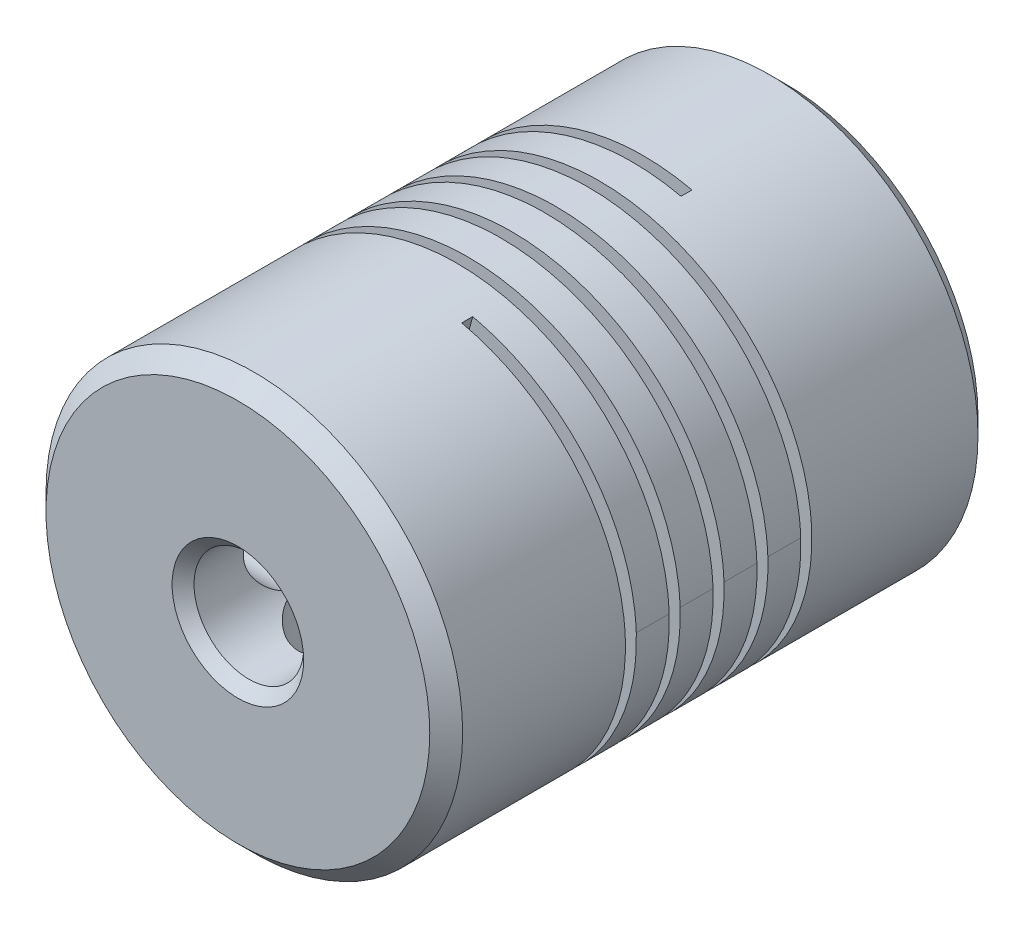
SolidWorks part; units mm, degrees
material "7075-T6 (SN)"
ref_plane "Спереди" through (0, 0, 0) normal (0, 0, 1) x (1, 0, 0)
ref_plane "Сверху" through (0, 0, 0) normal (0, 1, 0) x (1, 0, 0)
ref_plane "Справа" through (0, 0, 0) normal (1, 0, 0) x (0, 0, -1)
sketch "Эскиз1" plane through (0, 0, 0) normal (0, 0, 1) x (1, 0, 0)
  circle A0 centre (0, 0) radius 9.5
  dimension "D1" = 19
extrude "Body" add sketch "Эскиз1" along normal blind 25
sketch "Эскиз2" plane through (0, 0, 25) normal (0, 0, 1) x (1, 0, 0)
  circle A0 centre (0, 0) radius 2.5
  dimension "D1" = 5
extrude "RodHole" cut sketch "Эскиз2" against normal blind 42
chamfer "OuterChamfer" distance 0.75 angle 45 2 edges at (9.5, 0, 25) (9.5, 0, 0)
chamfer "InnerChamfer" distance 0.5 angle 45 2 edges at (2.5, 0, 25) (2.5, 0, 0)
sketch "Эскиз3" plane through (0, 0, 0) normal (1, 0, 0) x (0, 0, -1)
  circle A0 centre (-4.5, 0) radius 1.75
  circle A1 centre (-20.5, 0) radius 1.75
  dimension "D1" = 3.5
  dimension "D2" = 3.5
  dimension "D3" = 4.5
  dimension "D4" = 20.5
extrude "SetScrewHoles1" cut sketch "Эскиз3" against normal blind 12
cosmetic thread "Условное изображение резьбы1" parameters "D2"=4
cosmetic thread "Условное изображение резьбы2" parameters "D2"=4
sketch "Эскиз4" plane through (0, 0, 0) normal (0, 1, 0) x (1, 0, 0)
  circle A0 centre (0, -4.5) radius 1.75
  circle A1 centre (0, -20.5) radius 1.75
  dimension "D1" = 3.5
  dimension "D2" = 3.5
  dimension "D3" = 4.5
  dimension "D4" = 20.5
extrude "SetScrewHoles2" cut sketch "Эскиз4" against normal blind 12
cosmetic thread "Условное изображение резьбы3" parameters "D2"=4
cosmetic thread "Условное изображение резьбы4" parameters "D2"=4
ref_plane "ReferencePlane1" through (0, 0, 17) normal (0, 0, 1) x (1, 0, 0)
sketch "Эскиз6" plane through (0, 0, 17) normal (0, 0, 1) x (1, 0, 0)
  circle A0 centre (0, 0) radius 9.5
curve "SlotTrajectory" pitch 2 height 10 turns 5
ref_plane "ReferencePlane2" through (0, 0, 0) normal (0.9659, -0.2588, 0) x (0, 0, -1)
sketch "Эскиз7" plane through (0, 0, 0) normal (0.9659, -0.2588, 0) x (0, 0, -1)
  line L0 (-0.75, 9.5) -> (-24.25, 9.5) construction
  line L1 (-6.75, 10.0798) -> (-7.25, 10.0798)
  line L2 (-6.75, 10.0798) -> (-6.75, 1.4319)
  line L3 (-6.75, 1.4319) -> (-7.25, 1.4319)
  line L4 (-7.25, 10.0798) -> (-7.25, 1.4319)
  spline S0 degree 3 poles (-17, 9.5) (-16.9586, 9.5) (-16.8749, 9.0054) (-16.75, 6.8924) (-16.625, 3.7301) (-16.5, 0) (-16.375, -3.7301) (-16.25, -6.8924) (-16.125, -9.0054) (-16, -9.7473) (-15.875, -9.0054) (-15.75, -6.8924) (-15.625, -3.7301) (-15.5, 0) (-15.375, 3.7301) (-15.25, 6.8924) (-15.125, 9.0054) (-15, 9.7473) (-14.875, 9.0054) (-14.75, 6.8924) (-14.625, 3.7301) (-14.5, 0) (-14.375, -3.7301) (-14.25, -6.8924) (-14.125, -9.0054) (-14, -9.7473) (-13.875, -9.0054) (-13.75, -6.8924) (-13.625, -3.7301) (-13.5, 0) (-13.375, 3.7301) (-13.25, 6.8924) (-13.125, 9.0054) (-13, 9.7473) (-12.875, 9.0054) (-12.75, 6.8924) (-12.625, 3.7301) (-12.5, 0) (-12.375, -3.7301) (-12.25, -6.8924) (-12.125, -9.0054) (-12, -9.7473) (-11.875, -9.0054) (-11.75, -6.8924) (-11.625, -3.7301) (-11.5, 0) (-11.375, 3.7301) (-11.25, 6.8924) (-11.125, 9.0054) (-11, 9.7473) (-10.875, 9.0054) (-10.75, 6.8924) (-10.625, 3.7301) (-10.5, 0) (-10.375, -3.7301) (-10.25, -6.8924) (-10.125, -9.0054) (-10, -9.7473) (-9.875, -9.0054) (-9.75, -6.8924) (-9.625, -3.7301) (-9.5, 0) (-9.375, 3.7301) (-9.25, 6.8924) (-9.125, 9.0054) (-9, 9.7473) (-8.875, 9.0054) (-8.75, 6.8924) (-8.625, 3.7301) (-8.5, 0) (-8.375, -3.7301) (-8.25, -6.8924) (-8.125, -9.0054) (-8, -9.7473) (-7.875, -9.0054) (-7.75, -6.8924) (-7.625, -3.7301) (-7.5, 0) (-7.375, 3.7301) (-7.25, 6.8924) (-7.1251, 9.0054) (-7.0414, 9.5) (-7, 9.5) knots 0 0 0 0 0.0125 0.025 0.0375 0.05 0.0625 0.075 0.0875 0.1 0.1125 0.125 0.1375 0.15 0.1625 0.175 0.1875 0.2 0.2125 0.225 0.2375 0.25 0.2625 0.275 0.2875 0.3 0.3125 0.325 0.3375 0.35 0.3625 0.375 0.3875 0.4 0.4125 0.425 0.4375 0.45 0.4625 0.475 0.4875 0.5 0.5125 0.525 0.5375 0.55 0.5625 0.575 0.5875 0.6 0.6125 0.625 0.6375 0.65 0.6625 0.675 0.6875 0.7 0.7125 0.725 0.7375 0.75 0.7625 0.775 0.7875 0.8 0.8125 0.825 0.8375 0.85 0.8625 0.875 0.8875 0.9 0.9125 0.925 0.9375 0.95 0.9625 0.975 0.9875 1 1 1 1 construction
  point P0 (-7, 9.5)
  dimension "D1" = 0.5
  dimension "D2" = 0.25
sweep "Slot" cut profiles "Эскиз7" path "SlotTrajectory"
